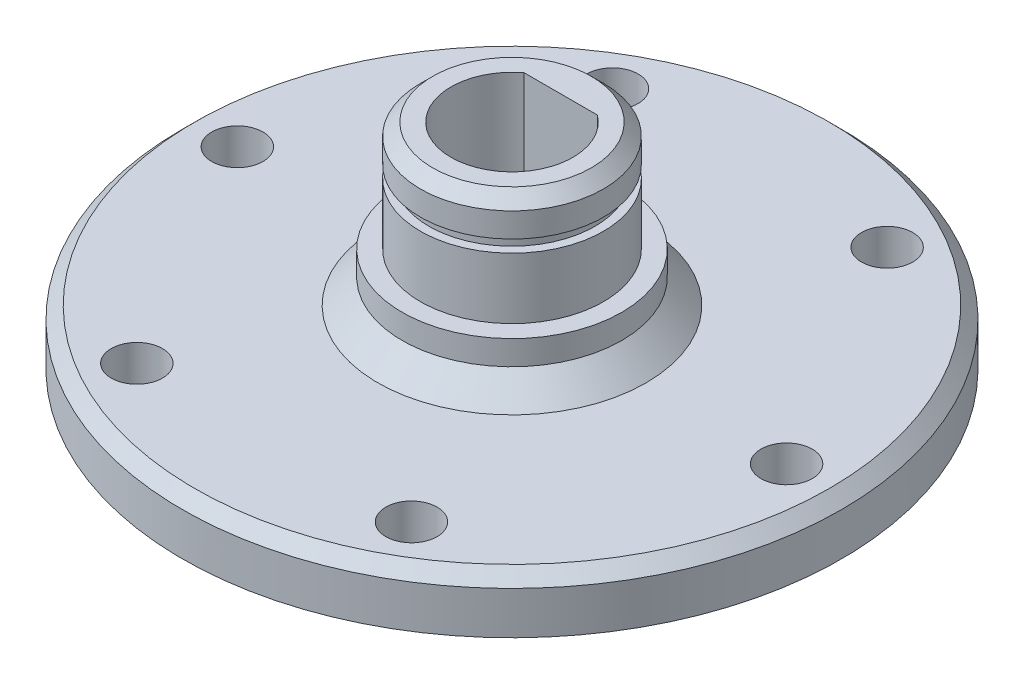
SolidWorks part; units mm, degrees
material "6061 合金"
ref_plane "前视基准面" through (0, 0, 0) normal (0, 0, 1) x (1, 0, 0)
ref_plane "上视基准面" through (0, 0, 0) normal (0, 1, 0) x (1, 0, 0)
ref_plane "右视基准面" through (0, 0, 0) normal (1, 0, 0) x (0, 0, -1)
sketch "草图1" plane through (0, 0, 0) normal (0, 0, 1) x (1, 0, 0)
  line L0 (0, 19) -> (0, 0)
  line L1 (10, 1.5) -> (27, 1.5)
  line L2 (27, 1.5) -> (27, 6)
  line L3 (27, 6) -> (9, 6)
  line L6 (9, 6) -> (9, 10)
  line L7 (9, 10) -> (7.5, 10)
  line L8 (7.5, 10) -> (7.5, 15)
  line L9 (7.5, 19) -> (0, 19)
  line L10 (10, 1.5) -> (10, 0)
  line L11 (10, 0) -> (0, 0)
  line L12 (7.5, 16) -> (7.5, 19)
  line L13 (7.5, 16) -> (6.8, 16)
  line L15 (7.5, 15) -> (6.8, 15)
  line L16 (6.8, 16) -> (6.8, 15)
  dimension "D1" = 4.5
  dimension "D2" = 27
  dimension "D3" = 7.5
  dimension "D4" = 9
  dimension "D5" = 1
  dimension "16" = 9
  dimension "D6" = 4
  dimension "D7" = 1.5
  dimension "D8" = 10
  dimension "D9" = 6.8
  dimension "D10" = 5
revolve "旋转1" add sketch "草图1" angle 360 about L0
sketch "草图2" plane through (0, 19, 0) normal (0, 1, 0) x (1, 0, 0)
  line L0 (-3, 4) -> (3, 4)
  arc A0 (-3, 4) -> (3, 4) centre (0, 0) ccw
  dimension "D1" = 10
  dimension "D2" = 4
extrude "切除-拉伸1" cut sketch "草图2" against normal through all
sketch "草图5" plane through (0, 19, 0) normal (0, 1, 0) x (1, 0, 0)
  line L0 (-2.6926, 7) -> (2.6926, 7)
  line L1 (3, 4) -> (-3, 4) construction
  circle A0 centre (0, 0) radius 7.5 construction
  circle A1 centre (0, 0) radius 7.5 construction
  arc A2 (2.6926, 7) -> (-2.6926, 7) centre (0, 0) ccw
  dimension "D1" = 3
extrude "切除-拉伸4" [suppressed] cut sketch "草图5" against normal up to surface (10 mm away)
sketch "草图3" plane through (0, 0, 0) normal (0, 0, 1) x (1, 0, 0)
  line L0 (7.5, 19) -> (-7.5, 19) construction
  circle A0 centre (0, 9.5) radius 1.25
  dimension "D1" = 2.5
  dimension "D2" = 9.5
extrude "切除-拉伸2" [suppressed] cut sketch "草图3" against normal through all both and the other way through all
cosmetic thread "装饰螺纹线1" [suppressed] parameters "D2"=3
sketch "草图4" plane through (0, 6, 0) normal (0, 1, 0) x (1, 0, 0)
  circle A0 centre (0, 0) radius 22.5 construction
  circle A1 centre (0, 22.5) radius 2.75
  circle A2 centre (19.4856, 11.25) radius 2.75
  circle A3 centre (19.4856, -11.25) radius 2.75
  circle A4 centre (0, -22.5) radius 2.75
  circle A5 centre (-19.4856, -11.25) radius 2.75
  circle A6 centre (-19.4856, 11.25) radius 2.75
  point P18 (0, 0)
  dimension "D1" = 45
  dimension "D2" = 6
  dimension "D3" = 5.5
extrude "切除-拉伸3" [suppressed] cut sketch "草图4" against normal up to next and the other way through all
hole_wizard "M5 螺纹孔1" positions "草图6" profile "草图7" tap size "M5" standard "GB" end condition through all
sketch "草图6" plane through (0, 6, 0) normal (0, 1, 0) x (1, 0, 0)
  circle A0 centre (0, 0) radius 22.5 construction
  point P0 (-11.25, 19.4856)
  point P10 (11.25, 19.4856)
  point P11 (22.5, 0)
  point P12 (11.25, -19.4856)
  point P13 (-11.25, -19.4856)
  point P14 (-22.5, 0)
  point P16 (0, 0)
  point P17 (13.9888, 17.6228)
  point P18 (-22.5, 0)
  dimension "D1" = 45
  dimension "D2" = 6
sketch "草图7" plane through (-11.25, 6, -19.4856) normal (1, 0, 0) x (0, 0, 1)
  line L0 (0, 0) -> (0, 6)
  line L1 (0, 6) -> (2.1, 6)
  line L2 (2.1, 6) -> (2.1, 0)
  line L5 (2.1, 0) -> (0, 0)
  line L11 (0, -6.35) -> (0, 107.95) construction
  dimension "通孔螺纹孔钻头直径" = 4.2
  dimension "通孔螺纹孔钻头深度" = 6
cosmetic thread "孔螺蚊线1" parameters "D2"=5
cosmetic thread "孔螺蚊线2" parameters "D2"=5
cosmetic thread "孔螺蚊线3" parameters "D2"=5
cosmetic thread "孔螺蚊线4" parameters "D2"=5
cosmetic thread "孔螺蚊线5" parameters "D2"=5
cosmetic thread "孔螺蚊线6" parameters "D2"=5
chamfer "倒角1" distance 2 angle 45 1 edges at (-9, 6, 0)
chamfer "倒角2" distance 1 angle 45 2 edges at (-27, 6, 0) (-7.5, 19, 0)
